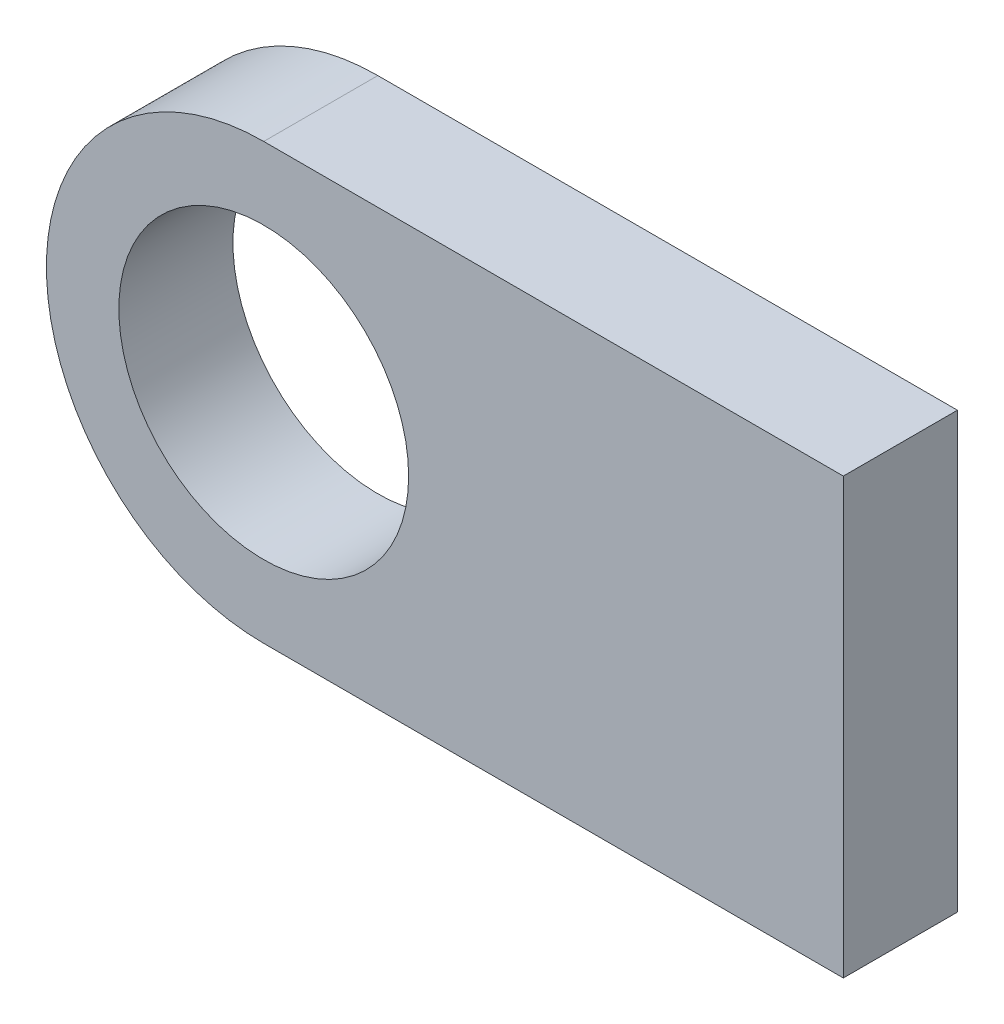
SolidWorks part; units mm, degrees
ref_plane "Front" through (0, 0, 0) normal (0, 0, 1) x (1, 0, 0)
ref_plane "Top" through (0, 0, 0) normal (0, 1, 0) x (1, 0, 0)
ref_plane "Right" through (0, 0, 0) normal (1, 0, 0) x (0, 0, -1)
other "Configuration Table"
sketch "Sketch1" plane through (0, 0, 0) normal (0, 0, 1) x (1, 0, 0)
  line L1 (0, 0) -> (50.8, 0)
  line L3 (0, 38.1) -> (50.8, 38.1)
  line L4 (50.8, 0) -> (50.8, 38.1)
  arc A0 (0, 38.1) -> (0, 0) centre (0, 19.05) ccw
  circle A1 centre (0, 19.05) radius 12.7
  dimension "D3" = 25.4
  dimension "D1" = 50.8
  dimension "D2" = 38.1
extrude "Extrude1" add sketch "Sketch1" against normal blind 10
